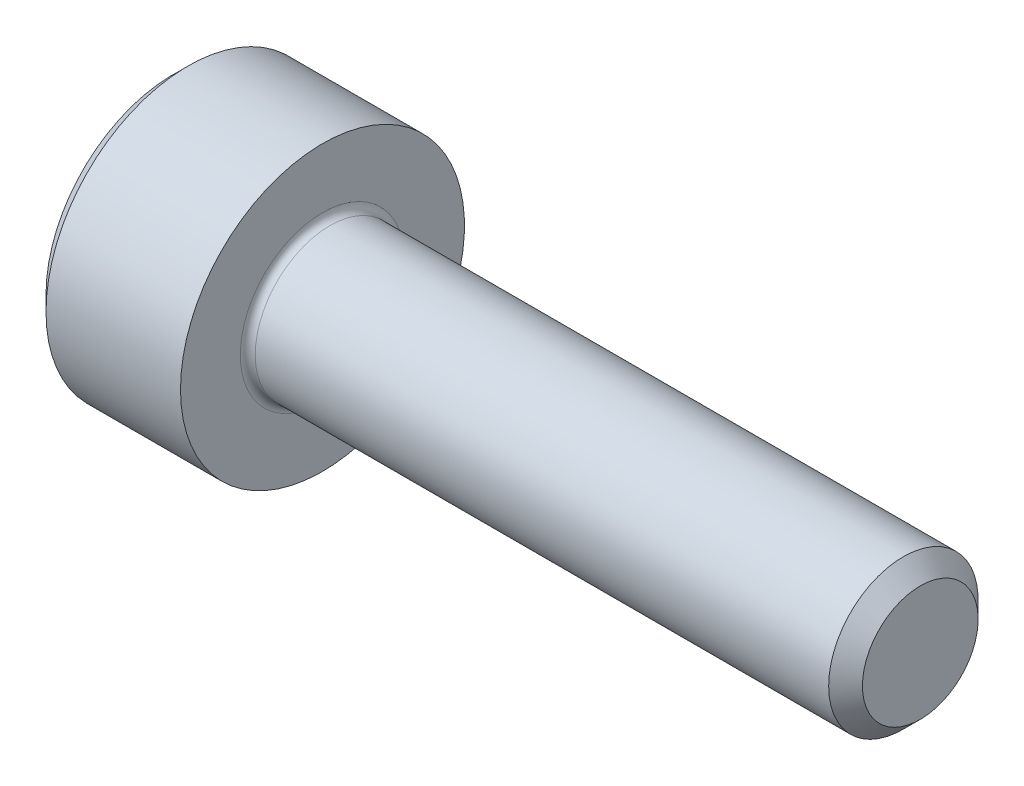
SolidWorks part; units mm, degrees
revolve "Base-Revolve" add sketch "BodySke"
sketch "BodySke" plane through (0, 0, 0) normal (0, 0, 1) x (1, 0, 0)
  line L0 (0, 0) -> (0, 1.7)
  line L1 (0.2, 1.9) -> (2, 1.9)
  line L2 (2, 1.9) -> (2, 1)
  line L3 (2, 1) -> (9.774, 1)
  line L4 (10, 0.774) -> (10, 0)
  line L5 (10, 0) -> (0, 0)
  line L6 (-31.75, 0) -> (127, 0) construction
  line L7 (0, 1.7) -> (0.2, 1.9)
  line L8 (10, 0.774) -> (9.774, 1)
  line L9 (0, -1.7) -> (0.2, -1.9) construction
  line L10 (10, -0.774) -> (9.774, -1) construction
  line L11 (2.4, 9.525) -> (2.4, 3.175) construction
  line L12 (2, 9.525) -> (2, 3.175) construction
  line L13 (-40, 9.525) -> (-40, 3.175) construction
  dimension "Diameter" = 2
  dimension "Head_ht" = 2
  dimension "Length" = 8
  dimension "Body_ch_ang" = 45
  dimension "Head_dia" = 3.8
  dimension "Head_ch_ang" = 45
  dimension "Minor_dia" = 1.548
  dimension "Advance" = 0.4
  dimension "Thread_nom" = 8
  dimension "Thread_length" = 50
  dimension "Head_ch_ht" = 0.2
cosmetic thread "ThreadCosmetic"
fillet "Fillet1" radius 0.1 1 edges at (2, 0, 1)
ref_plane "Plane1" through (0, 0, 0) normal (0, 0, 1) x (1, 0, 0)
ref_plane "Plane2" through (0, 0, 0) normal (0, 1, 0) x (1, 0, 0)
ref_plane "Plane3" through (0, 0, 0) normal (1, 0, 0) x (0, 0, -1)
sketch "Sketch2" plane through (0, 0, 0) normal (0, 0, 1) x (1, 0, 0)
  line L0 (0, 0.7725) -> (1, 0.7725)
  line L1 (1, 0.7725) -> (1.446, 0)
  line L2 (-31.75, 0) -> (127, 0) construction
  line L3 (1.446, 0) -> (0, 0)
  line L4 (0, 0) -> (0, 0.7725)
  line L5 (0, 1.7) -> (0, -1.7) construction
  line L6 (0, 0) -> (47.625, 0) construction
  line L7 (2, -1.9) -> (2, 1.9) construction
  dimension "D1" = 0.7725
  dimension "D2" = 60
revolve "Hex-PreBroach" cut sketch "Sketch2" angle 360 about L6
sketch "Sketch3" plane through (0, 0, 0) normal (-1, 0, 0) x (0, 0.5, 0.866)
  line L0 (0.446, 0.7725) -> (-0.446, 0.7725)
  line L1 (-0.446, 0.7725) -> (-0.892, 0)
  line L2 (0.446, 0.7725) -> (0.892, 0)
  line L3 (0.446, -0.7725) -> (0.892, 0)
  line L4 (0.446, -0.7725) -> (-0.446, -0.7725)
  line L5 (-0.446, -0.7725) -> (-0.892, 0)
  dimension "D1" = 0.7725
  dimension "D2" = 0.7725
  dimension "Hex_size" = 1.545
extrude "Hex" cut sketch "Sketch3" against normal blind 1
sketch "Sketch4" plane through (0, 0, 0) normal (-1, 0, 0) x (0, 0, 1)
  line L0 (0, 0) -> (0.9398, 0)
  line L1 (0, 0) -> (6.1484, 3.5498) construction
  line L2 (0, 0) -> (0.4699, 0.8139)
  line L3 (0.7832, 0.2175) -> (0.8962, 0.2828)
  line L4 (0.58, 0.5695) -> (0.693, 0.6348)
  arc A0 (0.7832, 0.2175) -> (0.58, 0.5695) centre (0, 0) ccw
  arc A1 (0.9398, 0) -> (0.8962, 0.2828) centre (0, 0) ccw
  arc A2 (0.4699, 0.8139) -> (0.693, 0.6348) centre (0, 0) cw
  dimension "D1" = 30
  dimension "D2" = 60
  dimension "Spline_p_dim" = 0.4064
  dimension "D3" = 0.2032
extrude "Spline" [suppressed] cut sketch "Sketch4" against normal blind 1
pattern_circular "CirPattern1" [suppressed] count 6 every 60
sketch "Sketch5" plane through (0, 0, 0) normal (0, 0, 1) x (1, 0, 0)
  line L0 (-31.75, 0) -> (127, 0) construction
  line L2 (0, 1.7) -> (0, -1.7) construction
  circle A0 centre (0.1, 0) radius 0.005
  dimension "Drilled_hole_dia" = 0.01
  dimension "Drilled_hole_loc" = 0.1
extrude "Hole" [suppressed] cut sketch "Sketch5" against normal through all and the other way through all
pattern_circular "Drilled-4" [suppressed] count 2 every 60
pattern_circular "Drilled-6" [suppressed] count 3 every 60
sketch "ThdSchSke" plane through (0, 0, 0) normal (0, 0, 1) x (1, 0, 0)
  line L0 (2.4, -0.774) -> (2.2418, -1)
  line L1 (2.4, -0.774) -> (2.5582, -1)
  line L2 (2.5582, -1) -> (2.5582, -1.25)
  line L3 (-3.175, 0) -> (5.1513, 0) construction
  line L5 (2.5582, -1.25) -> (2.2418, -1.25)
  line L6 (2.2418, -1.25) -> (2.2418, -1)
  line L7 (0, 1.7) -> (0, -1.7) construction
  dimension "Thread_minor" = 1.548
  dimension "Diameter" = 2
  dimension "Start" = 2.4
revolve "ThreadSchematic" [suppressed] cut sketch "ThdSchSke" angle 360 about L3
pattern_linear "ThdSchPat" [suppressed]
equation "\"D2@Sketch3\" = \"Hex_size@Sketch3\" / 2"
equation "\"D1@Sketch3\" = \"Hex_size@Sketch3\" / 2"
equation "\"D1@Sketch2\" = \"Hex_size@Sketch3\" / 2"
equation "\"D3@Sketch4\" = \"Spline_p_dim@Sketch4\" / 2"
equation "\"Thread_minor@ThreadCosmetic\"  =  \"Minor_dia@BodySke\""
equation "\"D2@CirPattern1\" = 360 / \"Num_teeth@CirPattern1\""
equation "\"Wall_thickness@Sketch2\" = \"Head_ht@BodySke\" - \"Key_eng@Hex\""
equation "\"Thread_length@ThreadCosmetic\" = ((sgn( (\"Length@BodySke\" - \"Advance@BodySke\" ) - \"Thread_nom@BodySke\" )-1)*( (\"Length@BodySke\" - \"Advance@BodySke\" ) - \"Thread_nom@BodySke\" ))/-2+ \"Thread_nom@BodySke\""
equation "\"Thread_minor@ThdSchSke\" = \"Minor_dia@BodySke\""
equation "\"Diameter@ThdSchSke\" = \"Diameter@BodySke\""
equation "\"Overcut@ThdSchSke\" = \"Diameter@BodySke\" * 1.25"
equation "\"Start@ThdSchSke\" = \"Head_ht@BodySke\" + \"Length@BodySke\" - \"Thread_length@ThreadCosmetic\"  '---Non-countersunk---"
equation "\"Num_threads@ThdSchPat\" = int( \"Thread_length@ThreadCosmetic\" / \"Advance@BodySke\" + 0.999 )  + 1"
equation "\"Advance@ThdSchPat\" = \"Thread_length@ThreadCosmetic\" /  (\"Num_threads@ThdSchPat\" - 1) 'relax it"
equation "\"Num_threads@ThdSchPat\" = \"Num_threads@ThdSchPat\" - sgn( \"Num_threads@ThdSchPat\" - 1) '---chamfered tips only---"
